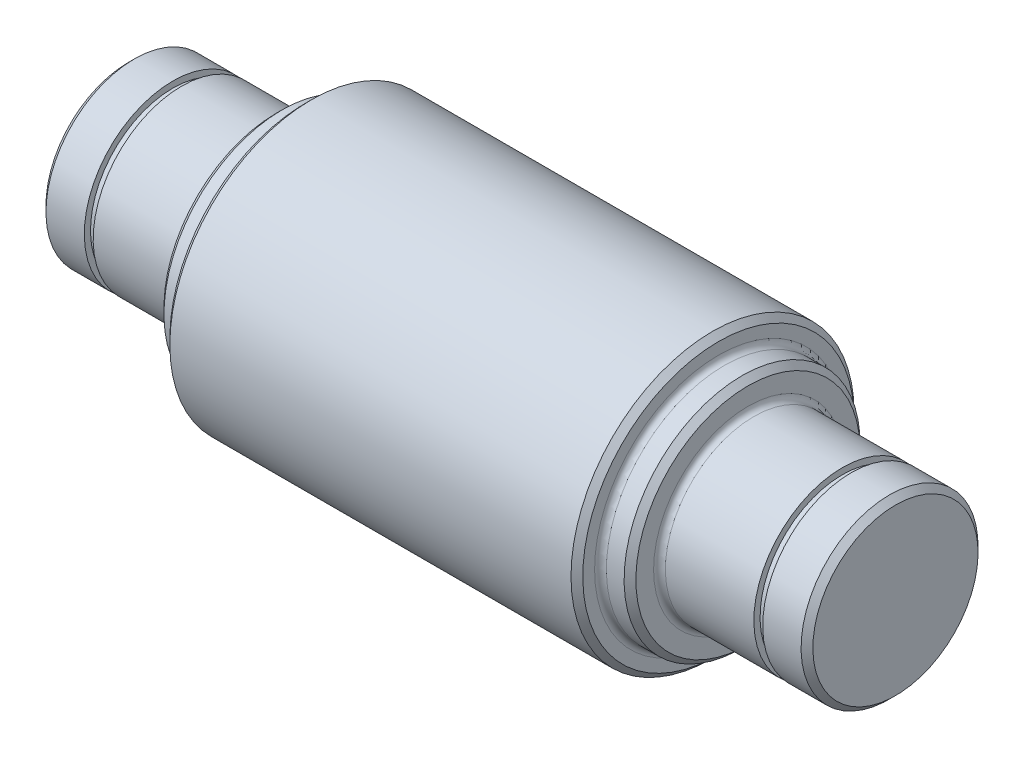
SolidWorks part; units mm, degrees
material "Plain Carbon Steel"
ref_plane "Front Plane" through (0, 0, 0) normal (0, 0, 1) x (1, 0, 0)
ref_plane "Top Plane" through (0, 0, 0) normal (0, 1, 0) x (1, 0, 0)
ref_plane "Right Plane" through (0, 0, 0) normal (1, 0, 0) x (0, 0, -1)
sketch "Sketch1" plane through (0, 0, 0) normal (0, 0, 1) x (1, 0, 0)
  line L0 (0, 0) -> (0, 24)
  line L1 (0, 24) -> (70, 24)
  line L2 (70, 24) -> (70, 20)
  line L3 (75, 15) -> (91, 15)
  line L4 (91, 15) -> (91, 13.95)
  line L5 (91, 13.95) -> (92.5, 13.95)
  line L6 (92.5, 13.95) -> (92.5, 15)
  line L7 (92.5, 15) -> (100, 15)
  line L8 (100, 15) -> (100, 0)
  line L9 (100, 0) -> (0, 0)
  line L10 (70, 20) -> (75, 20)
  line L11 (75, 20) -> (75, 15)
  dimension "D1" = 24
  dimension "D2" = 70
  dimension "D3" = 20
  dimension "D4" = 15
  dimension "D5" = 13.95
  dimension "D6" = 1.5
  dimension "D7" = 16
  dimension "D8" = 5
  dimension "D9" = 100
revolve "Revolve1" add sketch "Sketch1" angle 360 about L9
hole_wizard "M12 Tapped Hole1" positions "Sketch2" profile "Sketch3" tap size "M12" standard "DIN"
sketch "Sketch2" plane through (0, 0, 0) normal (-1, 0, 0) x (0, 0, 1)
  point P0 (0, 0)
sketch "Sketch3" plane through (0, 0, 0) normal (0, 1, 0) x (0, 0, 1)
  line L0 (0, 0) -> (0, 20)
  line L1 (0, 20) -> (5.1, 16.9356)
  line L2 (5.1, 16.9356) -> (5.1, 0.925)
  line L3 (5.1, 0.925) -> (6.025, 0)
  line L5 (6.025, 0) -> (0, 0)
  line L6 (-5.1, 0.925) -> (-6.025, 0) construction
  line L10 (0, 20) -> (-5.1, 16.9356) construction
  line L11 (0, -6.35) -> (0, 107.95) construction
  dimension "Tap Drill Dia." = 10.2
  dimension "Tap Drill Depth" = 20
  dimension "Near C'Sink Dia." = 12.05
  dimension "Near C'Sink Angle" = 90
  dimension "Drill Angle" = 118
cosmetic thread "Hole Thread1" parameters "D1"=24, "D2"=12
fillet "Fillet1" radius 1 2 edges at (75, 15, 0) (70, 20, 0)
chamfer "Chamfer1" distance 1 angle 45 4 edges at (75, 20, 0) (70, 24, 0) (0, 24, 0) (100, 15, 0)
scale "Scale1" scale about centroid uniform scaling yes scale factor 0.625
ref_plane "Plane1" through (37.9999, 0, 0) normal (-1, 0, 0) x (0, 0, 1)
mirror "Mirror2" about plane through (37.9999, 0, 0) normal (-1, 0, 0) of bodies 103
